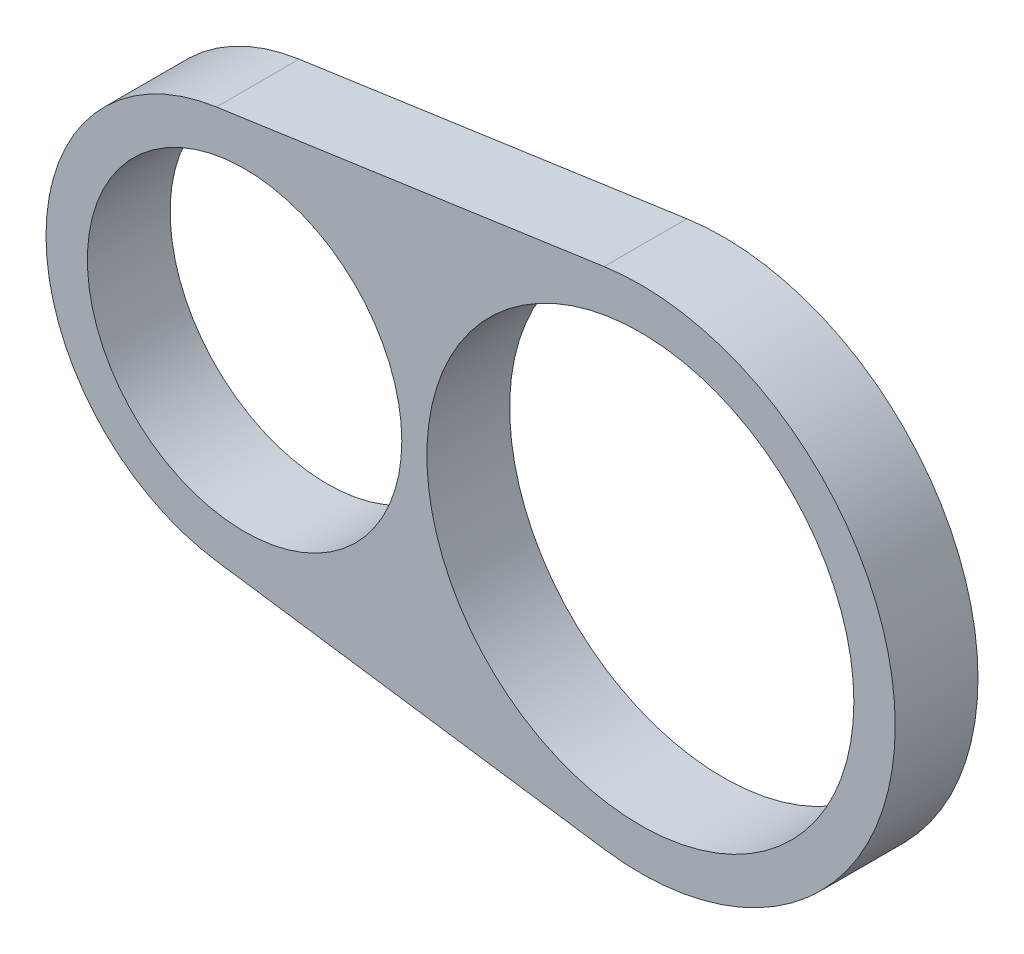
SolidWorks part; units mm, degrees
ref_plane "Plano frontal" through (0, 0, 0) normal (0, 0, 1) x (1, 0, 0)
ref_plane "Plano superior" through (0, 0, 0) normal (0, 1, 0) x (1, 0, 0)
ref_plane "Plano direito" through (0, 0, 0) normal (1, 0, 0) x (0, 0, -1)
sketch "Esboço1" plane through (0, 0, 0) normal (0, 0, 1) x (1, 0, 0)
  line L0 (-23.915, 0) -> (23.915, 0) construction
  line L1 (19.5362, 30.4871) -> (-27.3271, 23.7562)
  line L2 (-27.3271, -23.7562) -> (19.5362, -30.4871)
  circle A0 centre (23.915, 0) radius 25.8
  circle A1 centre (-23.915, 0) radius 19
  arc A2 (-27.3271, 23.7562) -> (-27.3271, -23.7562) centre (-23.915, 0) ccw
  circle A5 centre (-23.915, 0) radius 24 construction
  arc A6 (19.5362, -30.4871) -> (19.5362, 30.4871) centre (23.915, 0) ccw
  point P4 (0, 0)
  dimension "D1" = 5
extrude "Ressalto-extrusão1" add sketch "Esboço1" along normal blind 10
